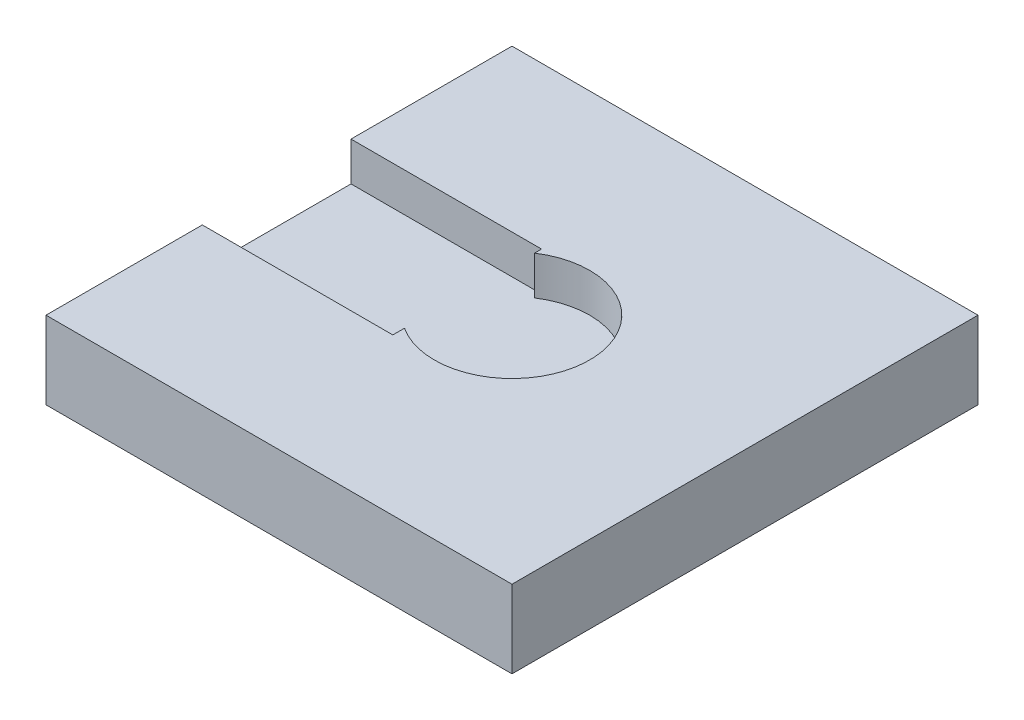
SolidWorks part; units mm, degrees
ref_plane "Ön Düzlem" through (0, 0, 0) normal (0, 0, 1) x (1, 0, 0)
ref_plane "Üst Düzlem" through (0, 0, 0) normal (0, 1, 0) x (1, 0, 0)
ref_plane "Sağ Düzlem" through (0, 0, 0) normal (1, 0, 0) x (0, 0, -1)
sketch "Sketch1" plane through (0, 0, 0) normal (0, 1, 0) x (1, 0, 0)
  line L1 (-30, 30) -> (30, 30)
  line L2 (-30, 30) -> (-30, -30)
  line L3 (-30, -30) -> (30, -30)
  line L4 (30, 30) -> (30, -30)
  line L5 (-30, 30) -> (30, -30) construction
  line L6 (-30, -30) -> (30, 30) construction
  point P0 (0, 0)
  dimension "D1" = 60
  dimension "D2" = 60
extrude "Boss-Extrude1" add sketch "Sketch1" along normal blind 10
sketch "Sketch3" plane through (0, 10, 0) normal (0, 1, 0) x (1, 0, 0)
  circle A0 centre (0, 0) radius 10
  dimension "D1" = 20
extrude "Cut-Extrude1" cut sketch "Sketch3" against normal blind 5
sketch "Sketch4" plane through (0, 10, 0) normal (0, 1, 0) x (1, 0, 0)
  line L0 (-30, 30) -> (-30, -30) construction
  line L1 (-5.4675, 9.2714) -> (-30, 9.2714)
  line L2 (-5.4675, 9.2714) -> (-5.4675, -9.8757)
  line L3 (-5.4675, -9.8757) -> (-30, -9.8757)
  line L4 (-30, 9.2714) -> (-30, -9.8757)
extrude "Cut-Extrude2" cut sketch "Sketch4" against normal blind 5
